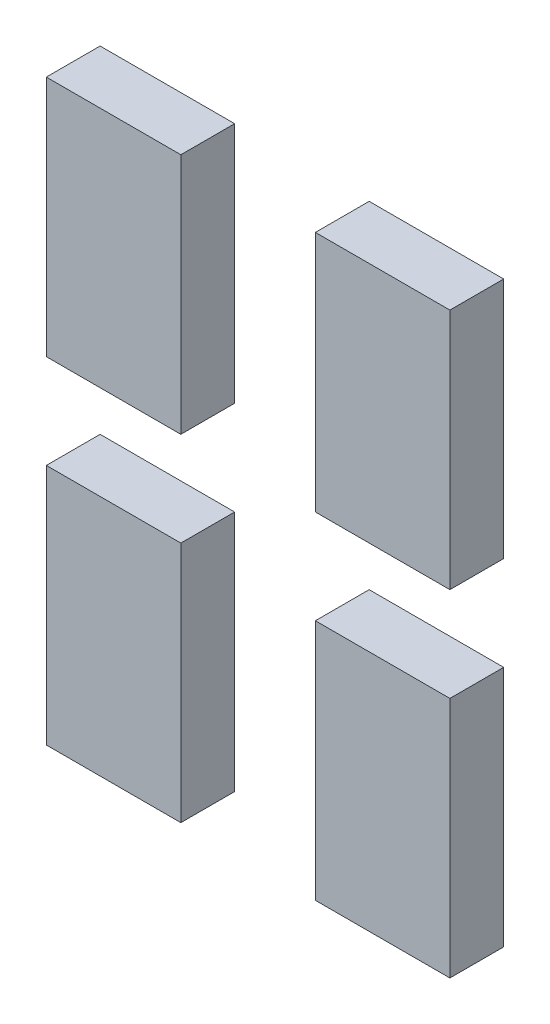
SolidWorks part; units mm, degrees
ref_plane "Спереди" through (0, 0, 0) normal (0, 0, 1) x (1, 0, 0)
ref_plane "Сверху" through (0, 0, 0) normal (0, 1, 0) x (1, 0, 0)
ref_plane "Справа" through (0, 0, 0) normal (1, 0, 0) x (0, 0, -1)
sketch "Эскиз1" plane through (0, 0, 0) normal (0, 0, 1) x (1, 0, 0)
  line L0 (3, -1.8) -> (5, -1.8)
  line L1 (-1, -1.8) -> (1, -1.8)
  line L2 (-1, -1.8) -> (-1, 1.8)
  line L3 (-1, 1.8) -> (1, 1.8)
  line L4 (1, -1.8) -> (1, 1.8)
  line L5 (-1, -1.8) -> (1, 1.8) construction
  line L6 (-1, 1.8) -> (1, -1.8) construction
  line L7 (5, -1.8) -> (5, 1.8)
  line L8 (3, 1.8) -> (5, 1.8)
  line L9 (3, -1.8) -> (3, 1.8)
  line L22 (3, 3.2) -> (5, 3.2)
  line L23 (5, 3.2) -> (5, 6.8)
  line L24 (3, 6.8) -> (5, 6.8)
  line L25 (3, 3.2) -> (3, 6.8)
  line L38 (-1, 3.2) -> (1, 3.2)
  line L39 (1, 3.2) -> (1, 6.8)
  line L40 (-1, 6.8) -> (1, 6.8)
  line L41 (-1, 3.2) -> (-1, 6.8)
  line L42 (7, -1.8) -> (9, -1.8) [skipped]
  line L43 (9, -1.8) -> (9, 1.8) [skipped]
  line L44 (7, 1.8) -> (9, 1.8) [skipped]
  line L45 (7, -1.8) -> (7, 1.8) [skipped]
  line L46 (11, -1.8) -> (13, -1.8) [skipped]
  line L47 (13, -1.8) -> (13, 1.8) [skipped]
  line L48 (11, 1.8) -> (13, 1.8) [skipped]
  line L49 (11, -1.8) -> (11, 1.8) [skipped]
  line L50 (15, -1.8) -> (17, -1.8) [skipped]
  line L51 (17, -1.8) -> (17, 1.8) [skipped]
  line L52 (15, 1.8) -> (17, 1.8) [skipped]
  line L53 (15, -1.8) -> (15, 1.8) [skipped]
  line L54 (7, 3.2) -> (9, 3.2) [skipped]
  line L55 (9, 3.2) -> (9, 6.8) [skipped]
  line L56 (7, 6.8) -> (9, 6.8) [skipped]
  line L57 (7, 3.2) -> (7, 6.8) [skipped]
  line L58 (11, 3.2) -> (13, 3.2) [skipped]
  line L59 (13, 3.2) -> (13, 6.8) [skipped]
  line L60 (11, 6.8) -> (13, 6.8) [skipped]
  line L61 (11, 3.2) -> (11, 6.8) [skipped]
  line L62 (15, 3.2) -> (17, 3.2) [skipped]
  line L63 (17, 3.2) -> (17, 6.8) [skipped]
  line L64 (15, 6.8) -> (17, 6.8) [skipped]
  line L65 (15, 3.2) -> (15, 6.8) [skipped]
  point P0 (0, 0)
  dimension "D1" = 2
  dimension "D2" = 3.6
  dimension "D3" = 5
  dimension "D4" = 2
extrude "Бобышка-Вытянуть1" add sketch "Эскиз1" along normal blind 0.8
